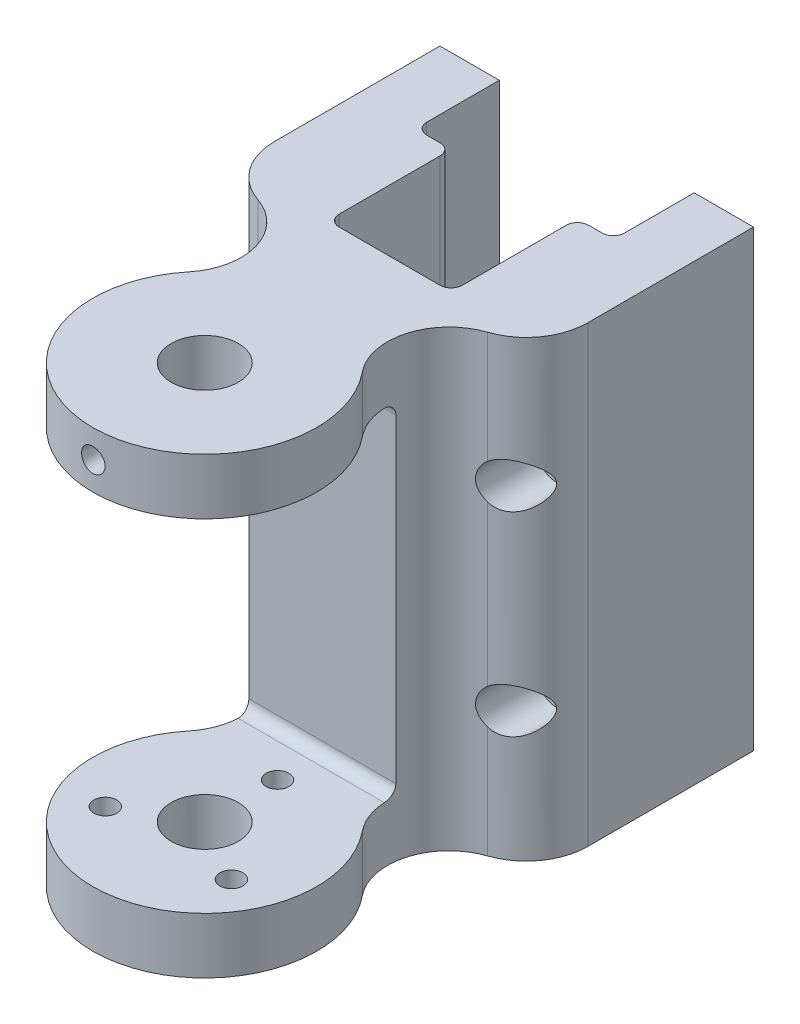
SolidWorks part; units mm, degrees
material "7075-T6 (SN)"
ref_plane "Face" through (0, 0, 0) normal (0, 0, 1) x (1, 0, 0)
ref_plane "Dessus" through (0, 0, 0) normal (0, 1, 0) x (1, 0, 0)
ref_plane "Droite" through (0, 0, 0) normal (1, 0, 0) x (0, 0, -1)
sketch "Esquisse3" plane through (0, 0, 0) normal (0, 1, 0) x (1, 0, 0)
  line L0 (-14, 0) -> (-14, -35)
  line L1 (0, 0) -> (0, -35) construction
  line L3 (14, -35) -> (14, 0)
  line L4 (-14, 0) -> (14, 0)
  line L6 (-14, 0) -> (-14, 3.841) construction
  line L7 (14, 0) -> (14, 6.0564) construction
  circle A0 centre (0, -35) radius 3
  arc A1 (-14, -35) -> (14, -35) centre (0, -35) ccw
  dimension "D2" = 6
  dimension "D1" = 28
  dimension "D4" = 35
extrude "Boss.-Extru.1" add sketch "Esquisse3" along normal mid plane 40.5
sketch "Esquisse5" plane through (0, 0, 0) normal (1, 0, 0) x (0, 0, -1)
  line L1 (-49, 15.25) -> (-24.5, 15.25)
  line L6 (-24.5, 15.25) -> (-24.5, -15.25)
  line L7 (-24.5, -15.25) -> (-49, -15.25)
  line L8 (-49, 20.25) -> (-49, -20.25) construction
  line L9 (-49, -15.25) -> (-49, 15.25)
  line L10 (-35, 20.25) -> (-49, 20.25) construction
  line L11 (-49, -20.25) -> (-35, -20.25) construction
  dimension "D1" = 5
  dimension "D2" = 5
  dimension "D3" = 24.5
extrude "Enlèv. mat.-Extru.2" cut sketch "Esquisse5" against normal through all and the other way through all
sketch "Esquisse6" plane through (0, -20.25, 0) normal (0, 1, 0) x (1, 0, 0)
  line L0 (-9, 0) -> (-9, -18) construction
  line L1 (-9, -18) -> (9, -18) construction
  line L2 (-8.7, 0) -> (-8.7, -7.4792)
  line L3 (-8.7, -7.4792) -> (-5.5, -7.4792)
  line L4 (-5.5, -7.4792) -> (-5.5, -18.5)
  line L5 (-5.5, -18.5) -> (5.5, -18.5)
  line L6 (5.5, -7.2219) -> (5.5, -18.5)
  line L7 (14, -35) -> (14, 0) construction
  line L8 (9, -18) -> (9, 0) construction
  line L9 (9, 0) -> (-9, 0) construction
  line L10 (5.5, -7.2219) -> (8.7, -7.2219)
  line L11 (0, 0) -> (0, -14.7927) construction
  line L12 (0, -35) -> (14, -26.9171) construction
  line L13 (-14, 0) -> (-14, -35) construction
  line L14 (8.7, -7.2219) -> (8.7, 0)
  line L15 (14, 0) -> (-14, 0) construction
  line L16 (8.7, 0) -> (-8.7, 0)
  dimension "D1" = 18
  dimension "D2" = 8.5
  dimension "D3" = 8.5
  dimension "D4" = 18
  dimension "D5" = 5
  dimension "D6" = 5.3
  dimension "D7" = 5.3
  dimension "D8" = 18.5
extrude "Enlèv. mat.-Extru.3" cut sketch "Esquisse6" against normal through all and the other way through all
sketch "Esquisse11" plane through (0, -20.25, 0) normal (0, -1, 0) x (1, 0, 0)
  line L0 (0, 49) -> (0, 14.7927) construction
  line L1 (-14, 0) -> (-14, 35) construction
  line L3 (14, 14.7927) -> (14, 35)
  line L4 (14, 35) -> (14, 0) construction
  line L5 (-14, 14.7927) -> (14, 14.7927) construction
  line L6 (-14, 14.7927) -> (-14, 35)
  arc A0 (7.7551, 28.6866) -> (-7.7551, 28.6866) centre (0, 35) ccw
  arc A1 (-10.2602, 20.0035) -> (-14, 14.7927) centre (-8.5, 14.7927) ccw
  arc A2 (7.7551, 28.6866) -> (10.2602, 20.0035) centre (12.0203, 25.2142) ccw
  arc A3 (14, 35) -> (-14, 35) centre (0, 35) ccw construction
  arc A4 (14, 35) -> (-14, 35) centre (0, 35) ccw
  arc A5 (-7.7551, 28.6866) -> (-10.2602, 20.0035) centre (-12.0203, 25.2142) cw
  arc A6 (10.2602, 20.0035) -> (14, 14.7927) centre (8.5, 14.7927) cw
  dimension "D1" = 20
  dimension "D2" = 5.5
extrude "Enlèv. mat.-Extru.6" cut sketch "Esquisse11" against normal through all
hole_wizard "Trou taraudé M2.51" positions "Esquisse13" profile "Esquisse12" tap size "M2.5" standard "DIN"
sketch "Esquisse13" plane through (0, -20.25, 0) normal (0, 1, 0) x (1, 0, 0)
  line L0 (0, -28.5) -> (-5.6292, -38.25)
  line L1 (-5.6292, -38.25) -> (5.6292, -38.25)
  line L2 (5.6292, -38.25) -> (0, -28.5)
  line L4 (-3, -35) -> (-6.5, -35) construction
  circle A0 centre (0, -35) radius 6.5
  circle A1 centre (0, -35) radius 3 construction
  point P6 (0, -28.5)
  point P7 (-5.6292, -38.25)
  point P9 (5.6292, -38.25)
  dimension "D1" = 13
sketch "Esquisse12" plane through (0, -20.25, 28.5) normal (1, 0, 0) x (0, 0, -1)
  line L0 (0, 0) -> (0, 5)
  line L1 (0, 5) -> (1.025, 5)
  line L2 (1.025, 5) -> (1.025, 0)
  line L5 (1.025, 0) -> (0, 0)
  line L11 (0, -6.35) -> (0, 107.95) construction
  dimension "Diamètre du trou pour taraudage jusqu'au prochain" = 2.05
  dimension "Profondeur du trou pour taraudage jusqu'au prochain" = 5
cosmetic thread "Filetage de perçage1" parameters "D1"=5, "D2"=2.5
cosmetic thread "Filetage de perçage2" parameters "D1"=5, "D2"=2.5
cosmetic thread "Filetage de perçage3" parameters "D1"=5, "D2"=2.5
ref_plane "Plan1" through (0, 0, 45) normal (0, 0, 1) x (1, 0, 0)
hole_wizard "Diamètre du perçage Ø2.1 (2.1)1" positions "Esquisse15" profile "Esquisse14" hole size "Ø2.1" standard "DIN"
sketch "Esquisse15" plane through (0, 0, 45) normal (0, 0, 1) x (1, 0, 0)
  line L0 (0, 20.25) -> (0, 15.25) construction
  line L4 (10, 20.25) -> (-10, 20.25) construction
  line L5 (-10, 15.25) -> (10, 15.25) construction
  point P0 (0, 17.75)
sketch "Esquisse14" plane through (0, 17.75, 45) normal (1, 0, 0) x (0, -1, 0)
  line L0 (0, 0) -> (0, 2.4309)
  line L1 (0, 2.4309) -> (1.05, 1.8)
  line L2 (1.05, 1.8) -> (1.05, 0)
  line L5 (1.05, 0) -> (0, 0)
  line L10 (0, 2.4309) -> (-1.05, 1.8) construction
  line L11 (0, -6.35) -> (0, 107.95) construction
  dimension "Diamètre du perçage" = 2.1
  dimension "Profondeur du perçage" = 1.8
  dimension "Angle de pointe" = 118
sketch "Esquisse16" plane through (0, 0, 0) normal (0, 0, -1) x (-1, 0, 0)
  line L0 (0, 23.0718) -> (0, -4.4703) construction
  line L4 (-17.4288, 0) -> (26.647, 0) construction
  circle A0 centre (-11.5, 8.7) radius 1.025
  circle A1 centre (11.5, 8.7) radius 1.025
  circle A2 centre (-11.5, -8.7) radius 1.025
  circle A3 centre (11.5, -8.7) radius 1.025
  dimension "D2" = 8.7
  dimension "D3" = 2.05
  dimension "D4" = 2.05
  dimension "D5" = 2.05
  dimension "D6" = 2.05
  dimension "D7" = 17.4
  dimension "D8" = 8.7
  dimension "D1" = 17.4
  dimension "D9" = 23
  dimension "D10" = 23
  dimension "D11" = 11.5
extrude "Enlèv. mat.-Extru.7" cut sketch "Esquisse16" against normal through all
sketch "Esquisse17" plane through (0, 0, 0) normal (0, 0, -1) x (-1, 0, 0)
  circle A0 centre (11.5, 8.7) radius 2
  circle A1 centre (11.5, -8.7) radius 2
  circle A2 centre (-11.5, -8.7) radius 2
  circle A3 centre (-11.5, 8.7) radius 2
  dimension "D1" = 4
  dimension "D2" = 4
  dimension "D3" = 4
  dimension "D4" = 4
extrude "Enlèv. mat.-Extru.9" cut sketch "Esquisse17" against normal blind 10 from offset 15 offset against normal yes
fillet "Congé1" radius 1 8 edges at (-5.5, 0, 18.5) (5.5, 0, 18.5) (-8.7, 0, 7.4792) (8.7, 0, 7.2219) (-5.5, 0, 7.4792) (5.5, 0, 7.2219) (0, 15.25, 24.5) (0, -15.25, 24.5)
